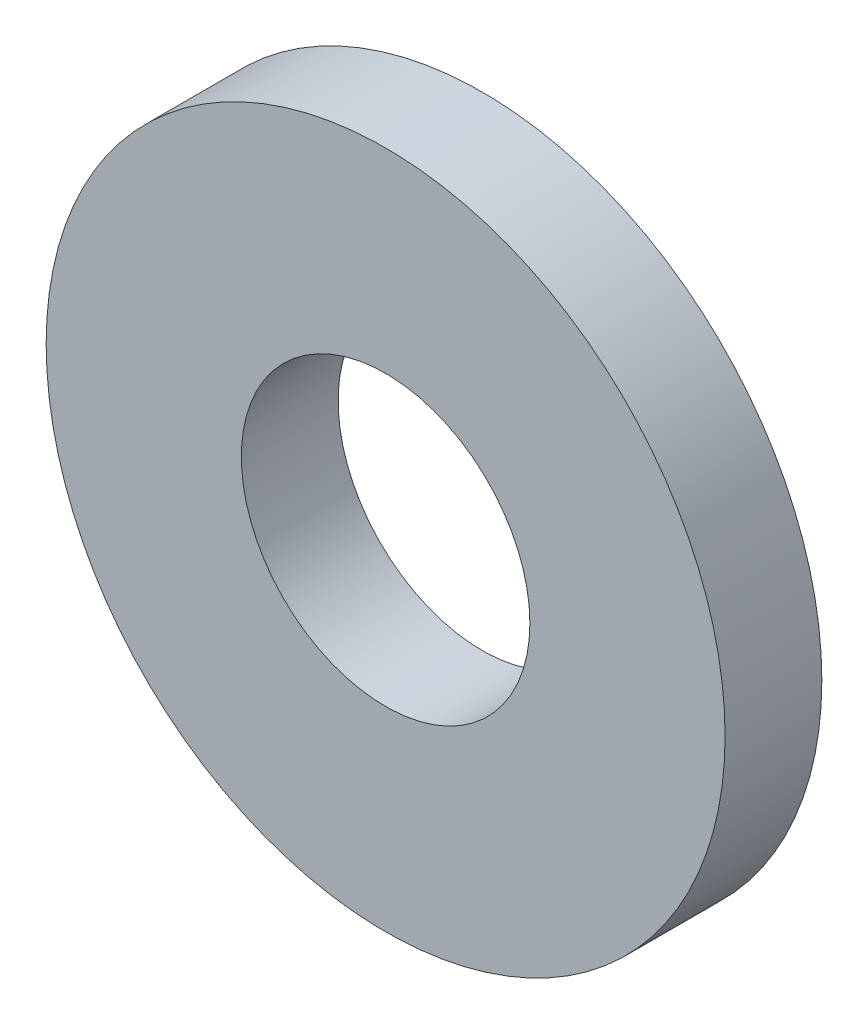
SolidWorks part; units mm, degrees
ref_plane "Front Plane" through (0, 0, 0) normal (0, 0, 1) x (1, 0, 0)
ref_plane "Top Plane" through (0, 0, 0) normal (0, 1, 0) x (1, 0, 0)
ref_plane "Right Plane" through (0, 0, 0) normal (1, 0, 0) x (0, 0, -1)
sketch "Sketch1" plane through (0, 0, 0) normal (0, 0, 1) x (1, 0, 0)
  line L0 (-20, 0) -> (20, 0) construction
  line L1 (0, -20) -> (0, 20) construction
  circle A0 centre (0, 0) radius 20
  circle A1 centre (0, 0) radius 8.5
  point P4 (0, 0)
  point P9 (0, 0)
  point P10 (0, -8.5)
  point P12 (-20, 0)
  point P13 (0, -20)
  dimension "ID" = 17
  dimension "OD" = 40
sketch "Sketch2" plane through (0, 0, 0) normal (1, 0, 0) x (0, 0, -1)
  line L0 (2.85, -20) -> (-2.85, -20) construction
  point P5 (0, -20)
  dimension "Thickness" = 5.7
sketch "Sketch3" plane through (0, 0, 0) normal (0, 0, 1) x (1, 0, 0)
  line L0 (0, -20) -> (0, 20) construction
  circle A0 centre (0, 0) radius 20
  circle A1 centre (0, 0) radius 8.5
  circle A2 centre (0, 0) radius 8.5 construction
extrude "Boss-Extrude1" add sketch "Sketch3" along normal mid plane 5.7
equation "\"D1@Boss-Extrude1\" = \"Thickness@Sketch2\""
